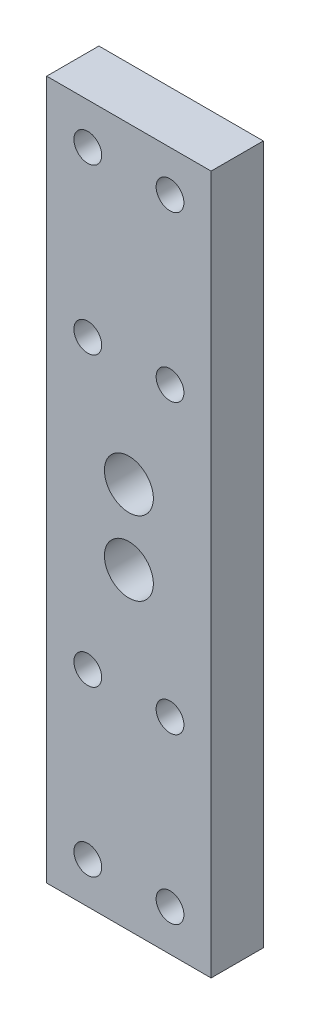
SolidWorks part; units mm, degrees
ref_plane "Alzado" through (0, 0, 0) normal (0, 0, 1) x (1, 0, 0)
ref_plane "Planta" through (0, 0, 0) normal (0, 1, 0) x (1, 0, 0)
ref_plane "Vista lateral" through (0, 0, 0) normal (1, 0, 0) x (0, 0, -1)
sketch "Croquis1" plane through (0, 0, 0) normal (0, 0, 1) x (1, 0, 0)
  line L1 (20, 85) -> (-20, 85)
  line L2 (20, 85) -> (20, -85)
  line L3 (20, -85) -> (-20, -85)
  line L4 (-20, 85) -> (-20, -85)
  line L5 (20, 85) -> (-20, -85) construction
  line L6 (20, -85) -> (-20, 85) construction
  point P0 (0, 0)
  dimension "D1" = 170
  dimension "D2" = 40
extrude "Saliente-Extruir1" add sketch "Croquis1" along normal mid plane 12.7
hole_wizard "Taladro de margen para 1/41" positions "Croquis2" profile "Croquis3" hole size "1/4" standard "Ansi Inch" end condition through all
sketch "Croquis2" plane through (0, 0, 6.35) normal (0, 0, 1) x (1, 0, 0)
  line L0 (0, 0) -> (-50000, 0) construction
  point P4 (10, 75)
  point P7 (10, 35)
  point P10 (-10, 35)
  point P13 (-10, 75)
  point P21 (-10, -75)
  point P22 (-10, -35)
  point P23 (10, -35)
  point P24 (10, -75)
sketch "Croquis3" plane through (10, 75, 6.35) normal (1, 0, 0) x (0, -1, 0)
  line L0 (0, 0) -> (0, 12.7)
  line L1 (0, 12.7) -> (3.3782, 12.7)
  line L2 (3.3782, 12.7) -> (3.3782, 0)
  line L5 (3.3782, 0) -> (0, 0)
  line L11 (0, -6.35) -> (0, 107.95) construction
  dimension "Diámetro de taladro hasta el siguiente" = 6.7564
  dimension "Profundidad de taladro hasta el siguiente" = 12.7
hole_wizard "Taladro de margen para 7/161" positions "Croquis4" profile "Croquis5" hole size "7/16" standard "Ansi Inch" end condition through all
sketch "Croquis4" plane through (0, 0, -6.35) normal (0, 0, -1) x (-1, 0, 0)
  point P0 (0, -9)
  point P5 (0, 9)
sketch "Croquis5" plane through (0, -9, -6.35) normal (1, 0, 0) x (0, 1, 0)
  line L0 (0, 0) -> (0, 12.7)
  line L1 (0, 12.7) -> (5.9525, 12.7)
  line L2 (5.9525, 12.7) -> (5.9525, 0)
  line L5 (5.9525, 0) -> (0, 0)
  line L11 (0, -6.35) -> (0, 107.95) construction
  dimension "Diámetro de taladro hasta el siguiente" = 11.905
  dimension "Profundidad de taladro hasta el siguiente" = 12.7
